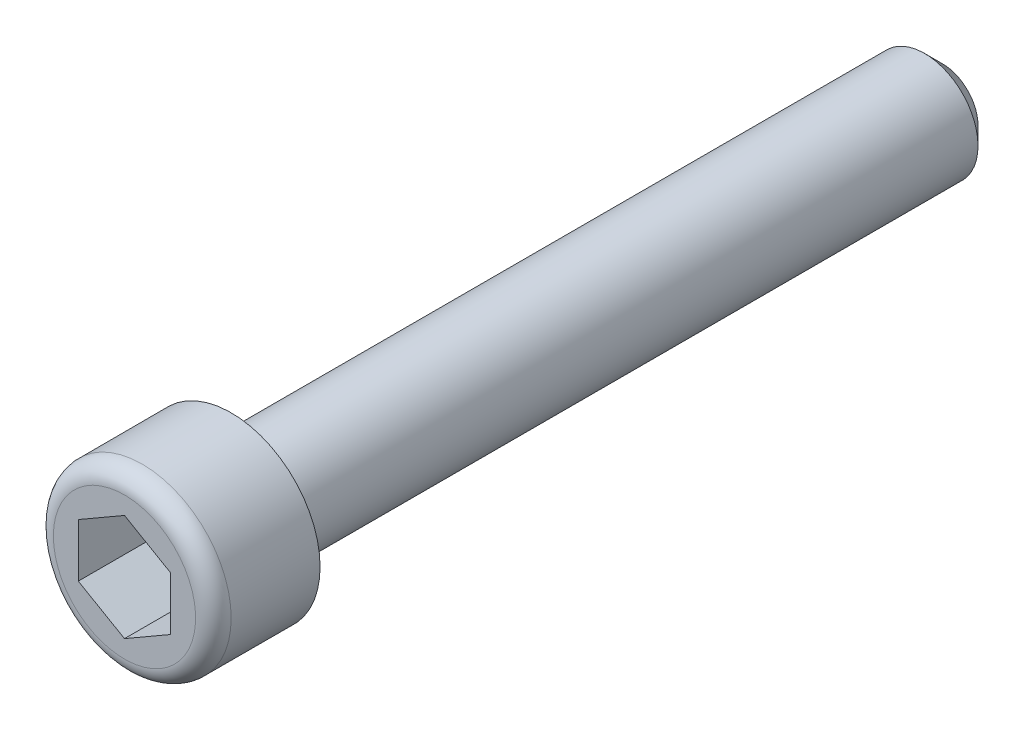
SolidWorks part; units mm, degrees
ref_plane "Front Plane" through (0, 0, 0) normal (0, 0, 1) x (1, 0, 0)
ref_plane "Top Plane" through (0, 0, 0) normal (0, 1, 0) x (1, 0, 0)
ref_plane "Right Plane" through (0, 0, 0) normal (1, 0, 0) x (0, 0, -1)
sketch "Sketch1" plane through (0, 0, 0) normal (1, 0, 0) x (0, 0, -1)
  line L0 (-156.2916, 0) -> (7658.2872, 0) construction
  line L1 (0, 0) -> (0, 5)
  line L2 (0, 5) -> (6, 5)
  line L3 (6, 5) -> (6, 3)
  line L4 (6, 3) -> (46, 3)
  line L5 (46, 3) -> (46, 0)
  line L6 (46, 0) -> (0, 0)
  dimension "D1" = 6
  dimension "D2" = 40
  dimension "D3" = 6
  dimension "D4" = 10
revolve "Body" add sketch "Sketch1" angle 360 about L0
sketch "Sketch2" plane through (0, 0, 0) normal (0, 0, 1) x (1, 0, 0)
  line L1 (0, 3) -> (-2.5981, 1.5)
  line L2 (-2.5981, 1.5) -> (-2.5981, -1.5)
  line L3 (-2.5981, -1.5) -> (0, -3)
  line L4 (0, -3) -> (2.5981, -1.5)
  line L5 (2.5981, -1.5) -> (2.5981, 1.5)
  line L6 (2.5981, 1.5) -> (0, 3)
  circle A0 centre (0, 0) radius 3 construction
  dimension "D1" = 6
extrude "Footprint" cut sketch "Sketch2" against normal blind 4.5
chamfer "Chamfer1" distance 1 angle 45 1 edges at (3, 0, -46)
fillet "Fillet1" radius 1 1 edges at (5, 0, 0)
